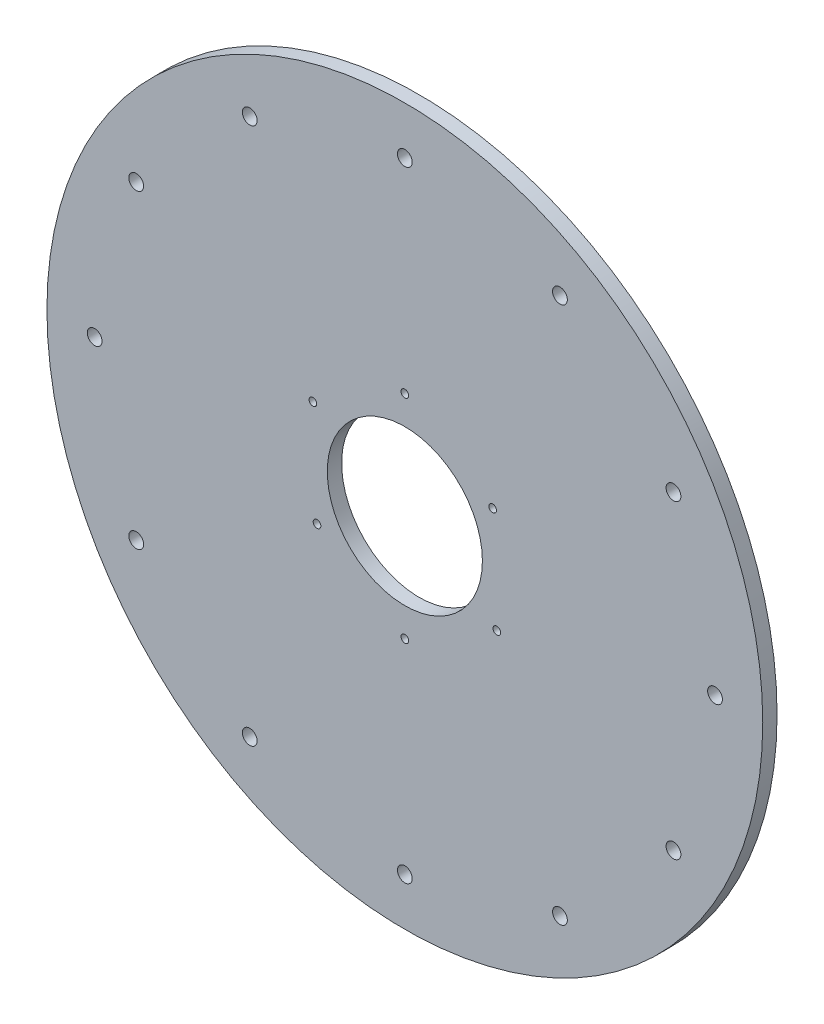
SolidWorks part; units mm, degrees
ref_plane "前视基准面" through (0, 0, 0) normal (0, 0, 1) x (1, 0, 0)
ref_plane "上视基准面" through (0, 0, 0) normal (0, 1, 0) x (1, 0, 0)
ref_plane "右视基准面" through (0, 0, 0) normal (1, 0, 0) x (0, 0, -1)
sketch "草图1" plane through (0, 0, 0) normal (0, 0, 1) x (1, 0, 0)
  line L0 (0, 44.5) -> (0, 0) construction
  line L1 (38.5381, 22.25) -> (-38.5381, -22.25) construction
  line L2 (0.0005, 0.0009) -> (-18.1759, 31.4834) construction
  circle A1 centre (0, 0) radius 32.5
  circle A3 centre (0, 0) radius 150
  circle A4 centre (0, 0) radius 130 construction
  circle A5 centre (0, 130) radius 3.1
  circle A6 centre (65, 112.5833) radius 3.1
  circle A7 centre (112.5833, 65) radius 3.1
  circle A8 centre (130, 0) radius 3.1
  circle A9 centre (112.5833, -65) radius 3.1
  circle A10 centre (65, -112.5833) radius 3.1
  circle A11 centre (0, -130) radius 3.1
  circle A12 centre (-65, -112.5833) radius 3.1
  circle A13 centre (-112.5833, -65) radius 3.1
  circle A14 centre (-130, 0) radius 3.1
  circle A15 centre (-112.5833, 65) radius 3.1
  circle A16 centre (-65, 112.5833) radius 3.1
  circle A17 centre (0, 0) radius 44.5 construction
  circle A18 centre (0, 44.5) radius 1.6
  circle A19 centre (0.0005, 0.0009) radius 44.5 construction
  circle A20 centre (0.0015, 0.0009) radius 44.5 construction
  circle A21 centre (0.002, 0) radius 44.5 construction
  circle A22 centre (0.0015, -0.0009) radius 44.5 construction
  circle A23 centre (0.0005, -0.0009) radius 44.5 construction
  circle A24 centre (38.5381, 22.25) radius 1.6 construction
  circle A25 centre (38.5381, -22.25) radius 1.6
  circle A26 centre (0, -44.5) radius 1.6
  circle A27 centre (-38.5381, -22.25) radius 1.6 construction
  circle A28 centre (-38.5381, 22.25) radius 1.6
  circle A32 centre (36.8068, 21.2504) radius 1.6
  circle A33 centre (-36.8053, -21.2496) radius 1.6
  point P31 (0, 0)
  point P48 (0.001, 0)
  point P59 (0, 0)
  dimension "D1" = 300
  dimension "D2" = 65
  dimension "D3" = 260
  dimension "D4" = 12
  dimension "D5" = 6.2
  dimension "D6" = 89
  dimension "D7" = 6
  dimension "D9" = 85
  dimension "D8" = 6
extrude "凸台-拉伸1" add sketch "草图1" along normal blind 6 contours A3
